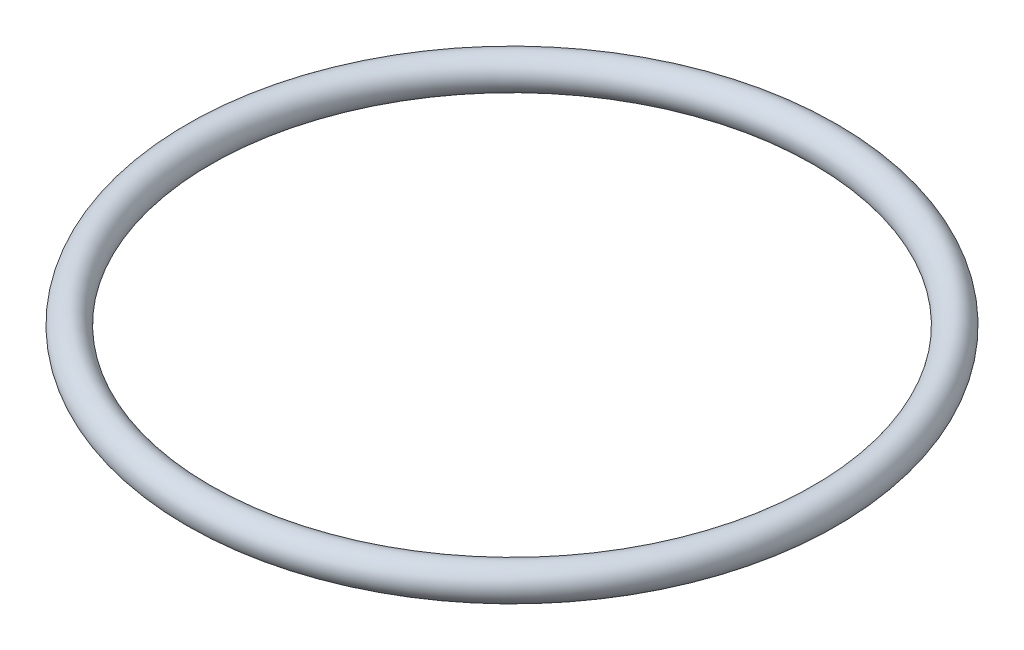
SolidWorks part; units mm, degrees
ref_plane "前视基准面" through (0, 0, 0) normal (0, 0, 1) x (1, 0, 0)
ref_plane "上视基准面" through (0, 0, 0) normal (0, 1, 0) x (1, 0, 0)
ref_plane "右视基准面" through (0, 0, 0) normal (1, 0, 0) x (0, 0, -1)
sketch "草图1" plane through (0, 0, 0) normal (0, 1, 0) x (1, 0, 0)
  circle A0 centre (0, 0) radius 28.5
  dimension "D1" = 57
sketch "草图2" plane through (0, 0, 0) normal (0, 0, 1) x (1, 0, 0)
  line L0 (0, 0) -> (-28.5, 0) construction
  line L1 (28.5, 0) -> (-28.5, 0) construction
  circle A0 centre (-28.5, 0) radius 1.5
  dimension "D2" = 3
  dimension "D1" = 28.5
sweep "扫描1" add profiles "草图2" path "草图1"
